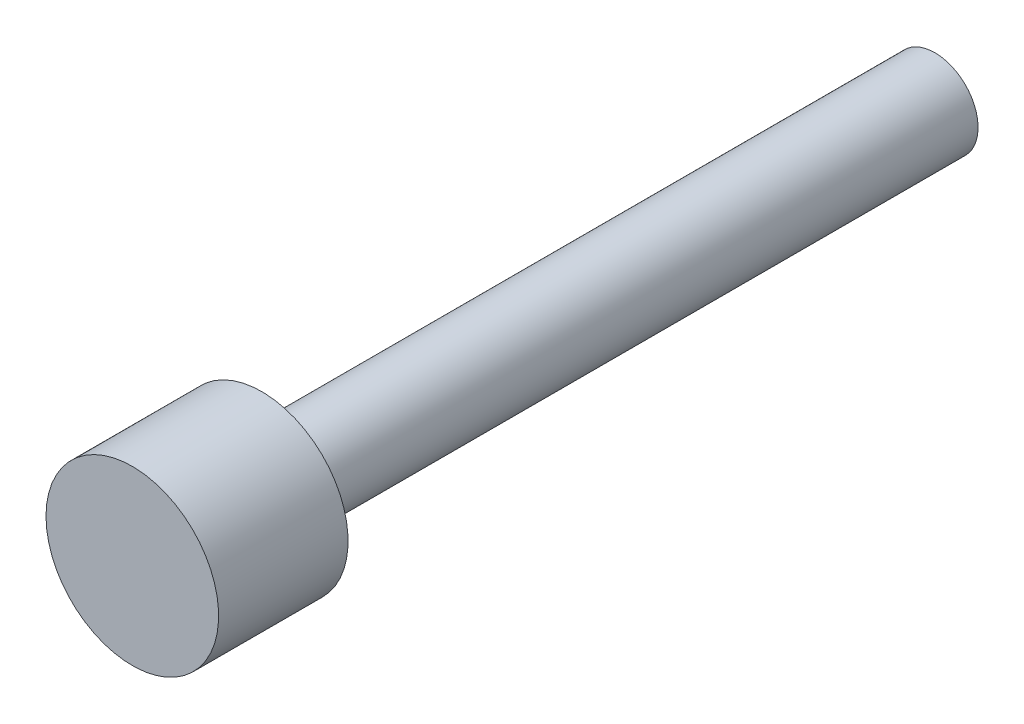
SolidWorks part; units mm, degrees
ref_plane "Front Plane" through (0, 0, 0) normal (0, 0, 1) x (1, 0, 0)
ref_plane "Top Plane" through (0, 0, 0) normal (0, 1, 0) x (1, 0, 0)
ref_plane "Right Plane" through (0, 0, 0) normal (1, 0, 0) x (0, 0, -1)
sketch "Sketch1" plane through (0, 0, 0) normal (0, 1, 0) x (1, 0, 0)
  line L0 (0, 0) -> (0, -465)
  line L1 (0, -465) -> (-50, -465)
  line L2 (-50, -465) -> (-50, -390)
  line L3 (-50, -390) -> (-25, -390)
  line L4 (-25, -390) -> (-25, 0)
  line L5 (-25, 0) -> (0, 0)
  dimension "D1" = 25
  dimension "D2" = 465
  dimension "D3" = 75
  dimension "D4" = 50
revolve "Revolve1" add sketch "Sketch1" angle 360 about L0
